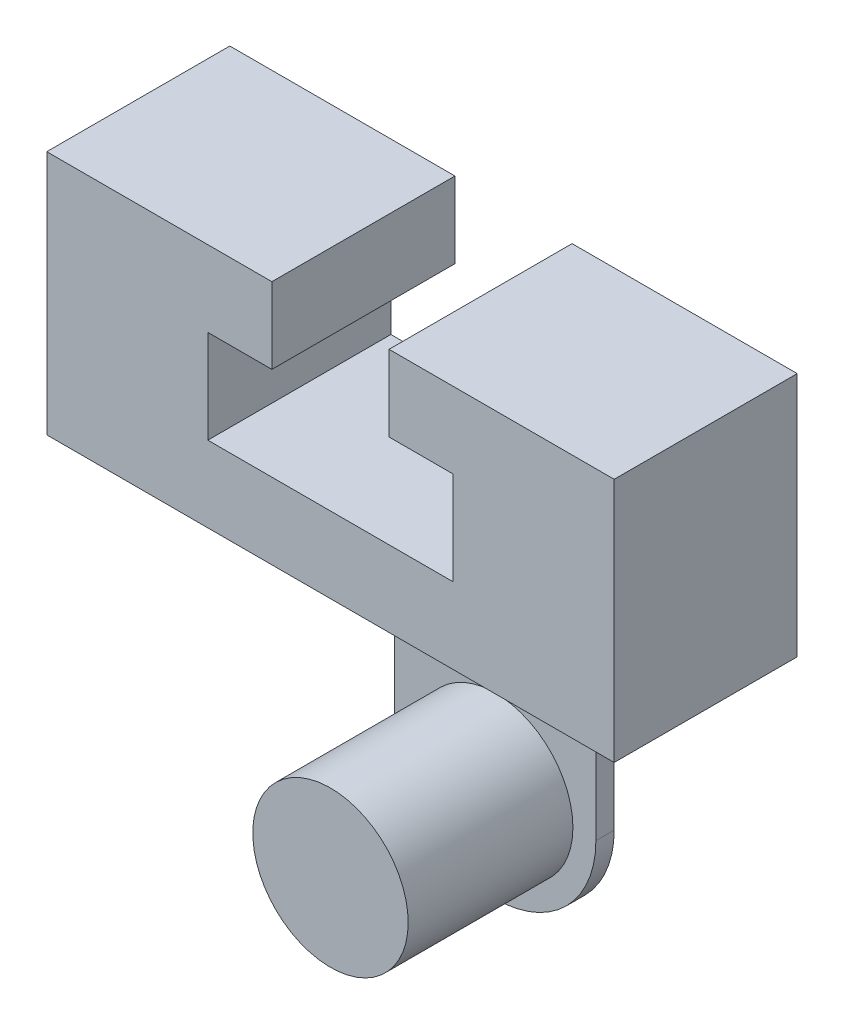
SolidWorks part; units mm, degrees
material "6061-T6 (SS)"
ref_plane "Front Plane" through (0, 0, 0) normal (0, 0, 1) x (1, 0, 0)
ref_plane "Top Plane" through (0, 0, 0) normal (0, 1, 0) x (1, 0, 0)
ref_plane "Right Plane" through (0, 0, 0) normal (1, 0, 0) x (0, 0, -1)
sketch "Sketch4" plane through (0, 0, 0) normal (0, 0, 1) x (1, 0, 0)
  line L0 (39.37, 0) -> (39.37, 34.036)
  line L1 (0, 0) -> (25.4, 0)
  line L2 (0, 0) -> (0, 34.036)
  line L3 (0, 34.036) -> (78.74, 34.036)
  line L4 (78.74, 0) -> (78.74, 34.036)
  line L5 (25.4, -33.528) -> (25.4, 0)
  line L6 (22.352, 10.541) -> (56.388, 10.541)
  line L7 (22.352, 10.541) -> (22.352, 23.495)
  line L8 (22.352, 23.495) -> (56.388, 23.495)
  line L9 (56.388, 10.541) -> (56.388, 23.495)
  line L10 (22.352, 10.541) -> (56.388, 23.495) construction
  line L11 (22.352, 23.495) -> (56.388, 10.541) construction
  line L12 (53.34, -33.528) -> (53.34, 0)
  line L13 (53.34, 0) -> (78.74, 0)
  arc A0 (25.4, -33.528) -> (53.34, -33.528) centre (39.37, -33.528) ccw
  point P7 (39.37, 17.018)
  point P13 (0, 0)
  dimension "D5" = 27.94
  dimension "D1" = 34.036
  dimension "D2" = 78.74
  dimension "D3" = 34.036
  dimension "D4" = 12.954
  dimension "D6" = 33.528
  dimension "D7" = 39.37
extrude "Boss-Extrude3" add sketch "Sketch4" along normal blind 25.4 separate body contours L5 L1 L2 L3 L4 L13 L12 A0
sketch "Sketch5" plane through (0, 0, 25.4) normal (0, 0, 1) x (1, 0, 0)
  line L0 (39.37, 34.036) -> (39.37, 0) construction
  line L1 (0, 34.036) -> (78.74, 34.036) construction
  line L2 (47.498, 23.495) -> (56.388, 23.495)
  line L3 (22.352, 10.541) -> (56.388, 10.541)
  line L4 (22.352, 10.541) -> (22.352, 23.495)
  line L5 (22.352, 23.495) -> (31.242, 23.495)
  line L6 (56.388, 10.541) -> (56.388, 23.495)
  line L7 (22.352, 10.541) -> (56.388, 23.495) construction
  line L8 (22.352, 23.495) -> (56.388, 10.541) construction
  line L10 (31.242, 23.495) -> (31.242, 34.036)
  line L11 (31.242, 34.036) -> (47.498, 34.036)
  line L12 (47.498, 23.495) -> (47.498, 34.036)
  point P5 (39.37, 17.018)
  dimension "D1" = 34.036
  dimension "D2" = 12.954
  dimension "D3" = 8.89
  dimension "D4" = 8.89
extrude "Cut-Extrude2" cut sketch "Sketch5" against normal through all
sketch "Sketch7" plane through (0, 0, 25.4) normal (0, 0, 1) x (1, 0, 0)
  line L1 (25.4, 0) -> (53.34, 0)
  line L2 (25.4, 0) -> (25.4, -33.528)
  line L4 (53.34, 0) -> (53.34, -33.528)
  arc A0 (25.4, -33.528) -> (53.34, -33.528) centre (39.37, -33.528) ccw
extrude "Cut-Extrude3" cut sketch "Sketch7" against normal blind 22.86
sketch "Sketch8" plane through (0, 0, 2.54) normal (0, 0, 1) x (1, 0, 0)
  circle A0 centre (39.37, -33.528) radius 10.7823
  dimension "D1" = 21.5646
extrude "Boss-Extrude4" add sketch "Sketch8" along normal blind 22.86
equation "\"F\"= 600"
equation "\"SF\"= 4"
equation "\"YM\"= 10000000"
equation "\"MaxDef\"= 0.005in"
equation "\"Length of Pin\"= 2"
equation "\"YS\"= 40000"
equation "\"Wofphi\"= 1.25"
equation "\"Le\"= 1.5"
equation "\"We\"= 3.1"
equation "\"Hb\"= 0.51"
equation "\"D_A\"= 0.849in"
equation "\"T_B\"= 0.137in"
equation "\"W_C\"= 1.342in"
equation "\"T_D\"= 0.0436in"
equation "\"Wa\"= 1"
equation "\"T_E\"= 1.342in"
equation "\"AllowStress\"= \"YS\" / \"SF\""
